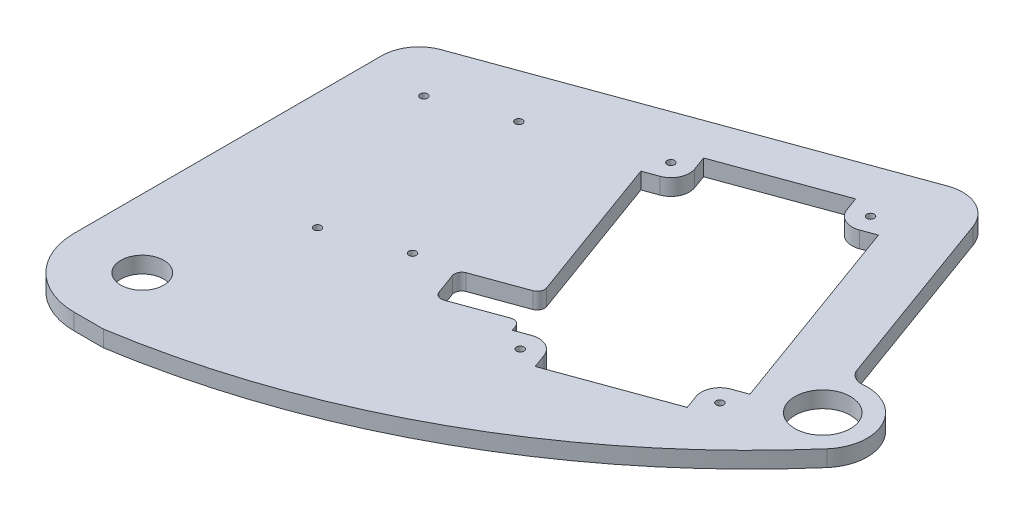
SolidWorks part; units mm, degrees
ref_plane "Front Plane" through (0, 0, 0) normal (0, 0, 1) x (1, 0, 0)
ref_plane "Top Plane" through (0, 0, 0) normal (0, 1, 0) x (1, 0, 0)
ref_plane "Right Plane" through (0, 0, 0) normal (1, 0, 0) x (0, 0, -1)
sketch "Sketch1" plane through (0, 0, 0) normal (0, 1, 0) x (1, 0, 0)
  line L4 (0, 0) -> (0, -240.03) construction
  line L5 (0, -240.03) -> (31.75, -240.03) construction
  line L6 (8.382, -240.03) -> (8.382, -125.73)
  line L7 (8.382, -125.73) -> (155.9475, -72.0206)
  line L9 (31.75, -263.398) -> (41.8376, -263.398)
  line L11 (184.5669, -150.6517) -> (155.9475, -72.0206)
  line L12 (0, 0) -> (189.7793, -164.9726) construction
  line L13 (189.7793, -164.9726) -> (184.5669, -150.6517) construction
  circle A3 centre (31.75, -240.03) radius 7.366
  arc A4 (41.8376, -263.398) -> (201.281, -174.9709) centre (0, 0) ccw
  arc A5 (8.382, -240.03) -> (31.75, -263.398) centre (31.75, -240.03) ccw
  circle A6 centre (189.7793, -164.9726) radius 9.525
  arc A7 (201.281, -174.9709) -> (184.5669, -150.6517) centre (189.7793, -164.9726) ccw
  dimension "D1" = 240.03
  dimension "D2" = 31.75
  dimension "D3" = 14.732
  dimension "D4" = 533.4
  dimension "D8" = 19.05
  dimension "D5" = 23.368
  dimension "D6" = 114.3
  dimension "D7" = 110
  dimension "D9" = 251.46
  dimension "D10" = 49
extrude "Boss-Extrude1" add sketch "Sketch1" along normal blind 5.588
sketch "Sketch2" plane through (0, 5.588, 0) normal (0, 1, 0) x (1, 0, 0)
  line L0 (83.0988, -113.7569) -> (116.1106, -204.456) construction
  line L1 (116.1106, -204.456) -> (175.781, -182.7378) construction
  line L2 (175.781, -182.7378) -> (142.7692, -92.0386) construction
  line L3 (142.7692, -92.0386) -> (83.0988, -113.7569) construction
  line L4 (159.2751, -137.3882) -> (154.5015, -139.1257) construction
  line L5 (99.6047, -159.1065) -> (104.3783, -157.369) construction
  line L6 (144.2083, -188.8233) -> (119.1467, -197.9449) construction
  line L7 (112.934, -102.8978) -> (114.6715, -107.6714) construction
  line L8 (119.1467, -197.9449) -> (104.3783, -157.369) construction
  line L9 (144.2083, -188.8233) -> (145.9458, -193.5969) construction
  line L10 (104.3783, -157.369) -> (89.6099, -116.7931) construction
  line L11 (89.6099, -116.7931) -> (114.6715, -107.6714) construction
  line L12 (114.6715, -107.6714) -> (139.7331, -98.5497) construction
  line L13 (139.7331, -98.5497) -> (154.5015, -139.1257) construction
  line L14 (154.5015, -139.1257) -> (169.2699, -179.7016) construction
  line L15 (169.2699, -179.7016) -> (144.2083, -188.8233) construction
  line L16 (155.9475, -72.0206) -> (8.382, -125.73) construction
  line L17 (175.781, -182.7378) -> (180.6732, -196.1787) construction
  line L18 (142.7692, -92.0386) -> (137.8771, -78.5976) construction
  circle A0 centre (169.2699, -179.7016) radius 1.27
  circle A1 centre (119.1467, -197.9449) radius 1.27
  circle A2 centre (89.6099, -116.7931) radius 1.27
  circle A3 centre (139.7331, -98.5497) radius 1.27
  arc A4 (41.8376, -263.398) -> (201.281, -174.9709) centre (0, 0) ccw construction
  circle A5 centre (31.75, -240.03) radius 7.366 construction
  dimension "D4" = 2.54
  dimension "D5" = 91.44
  dimension "D1" = 96.52
  dimension "D2" = 63.5
  dimension "D3" = 5.08
extrude "Cut-Extrude1" cut sketch "Sketch2" against normal through all and the other way through all
fillet "Fillet1" radius 12.7 2 edges at (8.382, 2.794, 125.73) (155.9475, 2.794, 72.0206)
fillet "Fillet2" radius 5.08 1 edges at (184.5669, 2.794, 150.6517)
sketch "Sketch3" plane through (0, 5.588, 0) normal (0, 1, 0) x (1, 0, 0)
  line L0 (169.2699, -179.7016) -> (163.1888, -162.9938) construction
  line L1 (163.1888, -162.9938) -> (139.7331, -98.5497) construction
  line L2 (163.1888, -162.9938) -> (150.0613, -167.7719) construction
  circle A1 centre (150.0613, -167.7719) radius 3.81
  dimension "D3" = 7.62
  dimension "D1" = 17.78
  dimension "D2" = 13.97
extrude "Cut-Extrude2" [suppressed] cut sketch "Sketch3" against normal through all
sketch "Sketch4" plane through (0, 5.588, 0) normal (0, 1, 0) x (1, 0, 0)
  line L0 (89.6099, -116.7931) -> (119.1467, -197.9449) construction
  line L1 (119.1467, -197.9449) -> (169.2699, -179.7016) construction
  line L2 (169.2699, -179.7016) -> (139.7331, -98.5497) construction
  line L3 (139.7331, -98.5497) -> (89.6099, -116.7931) construction
  line L4 (95.5769, -114.6213) -> (93.8395, -109.8476)
  line L5 (133.766, -100.7216) -> (132.0286, -95.9479)
  line L6 (93.8395, -109.8476) -> (132.0286, -95.9479)
  line L7 (125.1138, -195.7731) -> (126.8512, -200.5467)
  line L8 (163.3029, -181.8734) -> (165.0403, -186.647)
  line L9 (165.0403, -186.647) -> (126.8512, -200.5467)
  line L10 (116.9749, -191.9779) -> (112.2013, -193.7153)
  line L11 (91.7817, -122.7601) -> (87.0081, -124.4976)
  line L12 (87.0081, -124.4976) -> (112.2013, -193.7153)
  line L13 (141.9049, -104.5168) -> (146.6785, -102.7793)
  line L14 (167.0981, -173.7345) -> (171.8717, -171.9971)
  line L15 (171.8717, -171.9971) -> (146.6785, -102.7793)
  arc A0 (91.7817, -122.7601) -> (95.5769, -114.6213) centre (89.6099, -116.7931) ccw
  arc A1 (125.1138, -195.7731) -> (116.9749, -191.9779) centre (119.1467, -197.9449) ccw
  arc A2 (167.0981, -173.7345) -> (163.3029, -181.8734) centre (169.2699, -179.7016) ccw
  arc A3 (133.766, -100.7216) -> (141.9049, -104.5168) centre (139.7331, -98.5497) ccw
  dimension "D1" = 12.7
  dimension "D2" = 5.08
extrude "Cut-Extrude3" cut sketch "Sketch4" against normal through all
sketch "Sketch5" plane through (0, 5.588, 0) normal (0, 1, 0) x (1, 0, 0)
  line L0 (110.681, -189.5384) -> (89.1996, -197.357)
  line L1 (87.0081, -124.4976) -> (112.2013, -193.7153) construction
  line L2 (89.1996, -197.357) -> (84.856, -185.4229)
  line L3 (84.856, -185.4229) -> (106.3373, -177.6043)
  line L4 (106.3373, -177.6043) -> (110.681, -189.5384)
  line L5 (119.1467, -197.9449) -> (113.2828, -181.8339) construction
  line L6 (113.2828, -181.8339) -> (108.5092, -183.5714) construction
  dimension "D1" = 17.145
  dimension "D2" = 12.7
  dimension "D3" = 22.86
extrude "Cut-Extrude4" cut sketch "Sketch5" against normal through all
fillet "Fillet3" radius 2.54 4 edges at (84.856, 2.794, 185.4229) (89.1996, 2.794, 197.357) (110.681, 2.794, 189.5384) (106.3373, 2.794, 177.6043)
sketch "Sketch6" plane through (0, 5.588, 0) normal (0, 1, 0) x (1, 0, 0)
  line L0 (139.7331, -98.5497) -> (89.6099, -116.7931) construction
  line L1 (89.6099, -116.7931) -> (51.4208, -130.6928) construction
  line L2 (51.4208, -130.6928) -> (27.5526, -139.3801) construction
  line L3 (27.5526, -139.3801) -> (48.4021, -196.6638) construction
  line L4 (48.4021, -196.6638) -> (72.2703, -187.9764) construction
  line L5 (72.2703, -187.9764) -> (51.4208, -130.6928) construction
  circle A0 centre (51.4208, -130.6928) radius 1.27
  circle A1 centre (27.5526, -139.3801) radius 1.27
  circle A2 centre (48.4021, -196.6638) radius 1.27
  circle A3 centre (72.2703, -187.9764) radius 1.27
  circle A4 centre (119.1467, -197.9449) radius 1.27 construction
  dimension "D1" = 40.64
  dimension "D2" = 25.4
  dimension "D3" = 60.96
extrude "Cut-Extrude5" cut sketch "Sketch6" against normal through all
